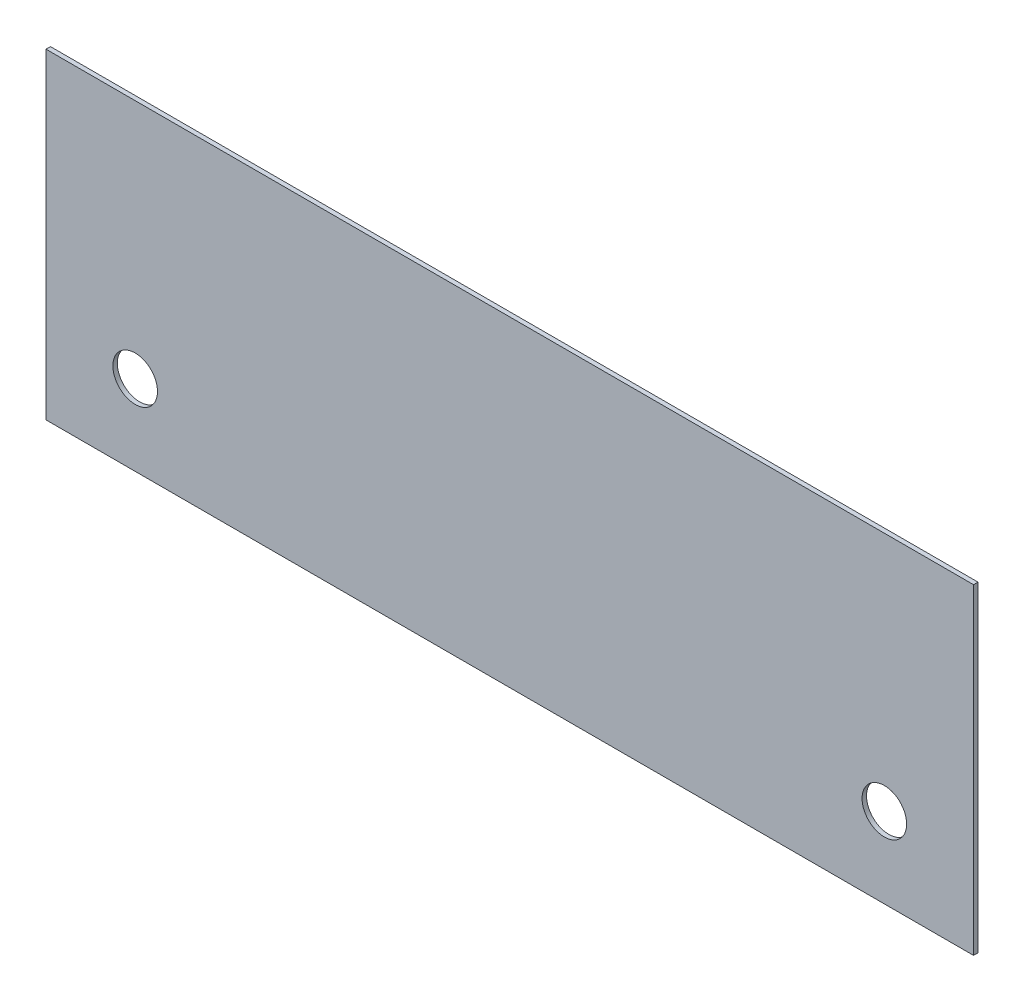
SolidWorks part; units mm, degrees
ref_plane "前视基准面" through (0, 0, 0) normal (0, 0, 1) x (1, 0, 0)
ref_plane "上视基准面" through (0, 0, 0) normal (0, 1, 0) x (1, 0, 0)
ref_plane "右视基准面" through (0, 0, 0) normal (1, 0, 0) x (0, 0, -1)
sketch "草图1" plane through (0, 0, 0) normal (0, 0, 1) x (1, 0, 0)
  line L1 (-52, -39) -> (52, -39)
  line L2 (-52, -39) -> (-52, -3)
  line L3 (-52, -3) -> (52, -3)
  line L4 (52, -39) -> (52, -3)
  line L5 (-52, -39) -> (52, -3) construction
  line L6 (-52, -3) -> (52, -39) construction
  point P0 (0, -21)
  dimension "D1" = 52
  dimension "D2" = 3
  dimension "D3" = 21
extrude "间隙补偿垫片_承力面接触" add sketch "草图1" along normal blind 0.5
sketch "草图2" plane through (0, 0, 0) normal (0, 0, 1) x (1, 0, 0)
  circle A0 centre (-42, -30) radius 2.5
  circle A1 centre (42, -30) radius 2.5
  dimension "D1" = 5
  dimension "D2" = 42
  dimension "D3" = 42
  dimension "D4" = 30
extrude "垫片穿孔" cut sketch "草图2" along normal blind 0.5
